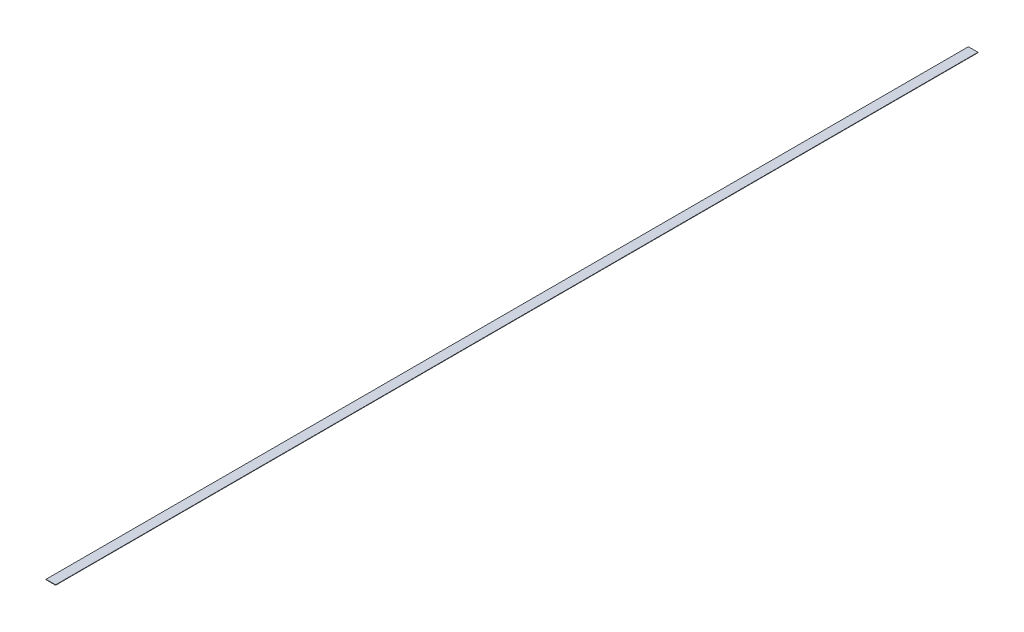
SolidWorks part; units mm, degrees
ref_plane "Front" through (0, 0, 0) normal (0, 0, 1) x (1, 0, 0)
ref_plane "Top" through (0, 0, 0) normal (0, 1, 0) x (1, 0, 0)
ref_plane "Right" through (0, 0, 0) normal (1, 0, 0) x (0, 0, -1)
sketch "Sketch1" plane through (0, 0, 0) normal (0, 1, 0) x (1, 0, 0)
  line L0 (0, 914.4) -> (0, -914.4)
  dimension "D1" = 1828.8
extrude "Extrude-Thin1" add sketch "Sketch1" along normal blind 0.7937 thin thin type mid plane wall 19.05
